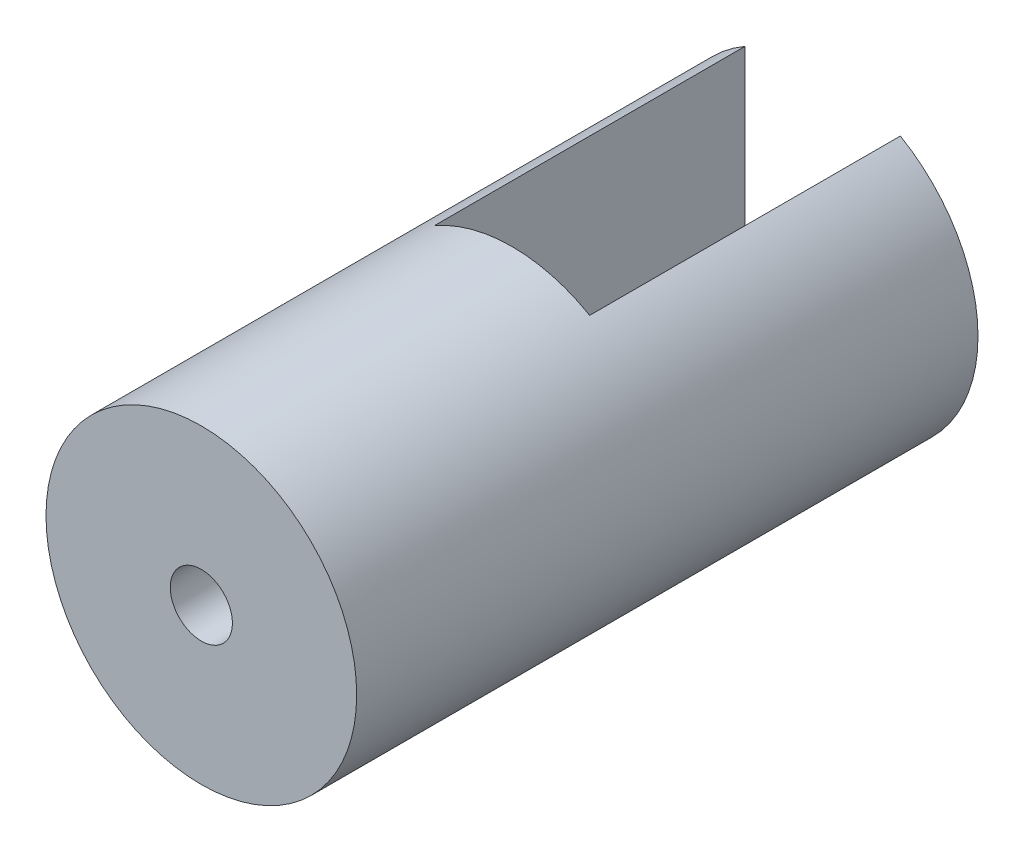
SolidWorks part; units mm, degrees
ref_plane "Alzado" through (0, 0, 0) normal (0, 0, 1) x (1, 0, 0)
ref_plane "Planta" through (0, 0, 0) normal (0, 1, 0) x (1, 0, 0)
ref_plane "Vista lateral" through (0, 0, 0) normal (1, 0, 0) x (0, 0, -1)
sketch "Croquis1" plane through (0, 0, 0) normal (0, 0, 1) x (1, 0, 0)
  circle A0 centre (0, 0) radius 5
extrude "Saliente-Extruir1" add sketch "Croquis1" along normal blind 20
sketch "Croquis3" plane through (0, 0, 0) normal (0, 0, -1) x (-1, 0, 0)
  line L0 (-2.5, 5) -> (2.5, 5)
  line L1 (2.5, 5) -> (2.5, -5)
  line L2 (2.5, -5) -> (-2.5, -5)
  line L3 (-2.5, -5) -> (-2.5, 5)
extrude "Cortar-Extruir1" cut sketch "Croquis3" against normal blind 10
ref_plane "Plano1" through (2.5, -4.3301, 10) normal (0, 0, -1) x (-1, 0, 0)
sketch "Croquis4" plane through (2.5, -4.3301, 10) normal (0, 0, -1) x (-1, 0, 0)
  circle A0 centre (2.5, 4.3301) radius 1
extrude "Cortar-Extruir2" cut sketch "Croquis4" against normal blind 10
